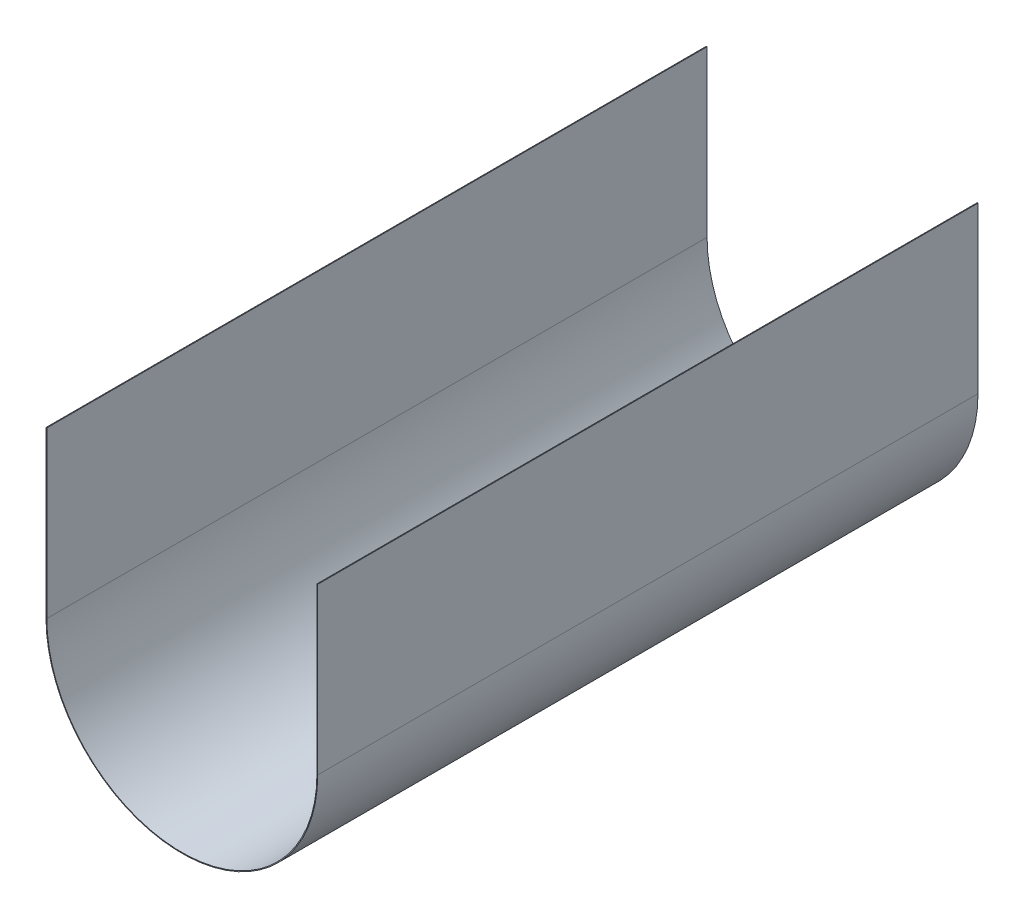
SolidWorks part; units mm, degrees
ref_plane "Front Plane" through (0, 0, 0) normal (0, 0, 1) x (1, 0, 0)
ref_plane "Top Plane" through (0, 0, 0) normal (0, 1, 0) x (1, 0, 0)
ref_plane "Right Plane" through (0, 0, 0) normal (1, 0, 0) x (0, 0, -1)
sketch "Sketch1" plane through (0, 0, 0) normal (0, 0, 1) x (1, 0, 0)
  line L0 (-344.9, 0) -> (-344.9, 419.1)
  line L2 (-342.9, 0) -> (-342.9, 419.1)
  line L3 (-342.9, 419.1) -> (342.9, 419.1)
  line L4 (342.9, 0) -> (342.9, 419.1)
  line L6 (344.9, 0) -> (344.9, 419.1)
  line L7 (-342.9, 419.1) -> (-344.9, 419.1)
  line L8 (342.9, 419.1) -> (344.9, 419.1)
  line L10 (344.9, 0) -> (344.9, 421.1) construction
  line L11 (-344.9, 421.1) -> (344.9, 421.1) construction
  line L12 (-344.9, 0) -> (-344.9, 421.1) construction
  arc A0 (-342.9, 0) -> (342.9, 0) centre (0, 0) ccw
  arc A1 (-344.9, 0) -> (344.9, 0) centre (0, 0) ccw
  dimension "D1" = 685.8
  dimension "D2" = 2
extrude "Boss-Extrude1" add sketch "Sketch1" along normal blind 1676.4 contours L0 A1 L6 L8 L4 A0 L2 L7
